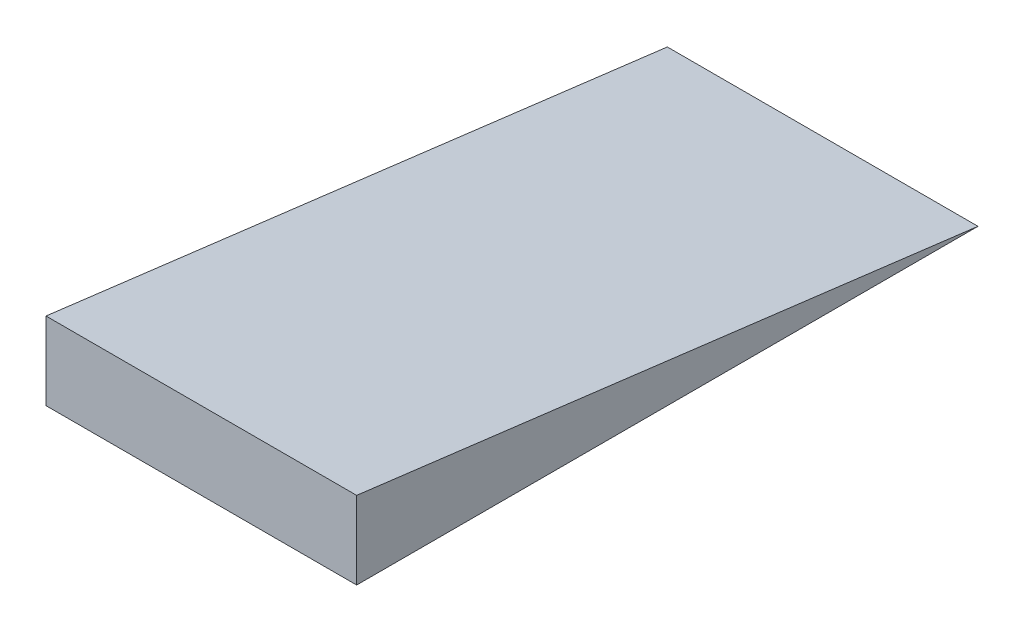
SolidWorks part; units mm, degrees
ref_plane "前视基准面" through (0, 0, 0) normal (0, 0, 1) x (1, 0, 0)
ref_plane "上视基准面" through (0, 0, 0) normal (0, 1, 0) x (1, 0, 0)
ref_plane "右视基准面" through (0, 0, 0) normal (1, 0, 0) x (0, 0, -1)
sketch "草图1" plane through (0, 0, 0) normal (1, 0, 0) x (0, 0, -1)
  line L0 (0, 100) -> (0, -100)
  line L1 (0, -100) -> (1600, -100)
  line L2 (1600, -100) -> (0, 100)
  point P4 (0, 0)
  dimension "D1" = 200
  dimension "D2" = 1600
extrude "凸台-拉伸1" add sketch "草图1" along normal blind 800
sketch "草图4" plane through (0, 98.4615, -12.3077) normal (0, 0.9923, -0.124) x (1, 0, 0)
  line L0 (400, 1600.0481) -> (400, -12.4035) construction
  line L1 (800, 1600.0481) -> (0, 1600.0481) construction
  line L2 (800, -12.4035) -> (0, -12.4035) construction
